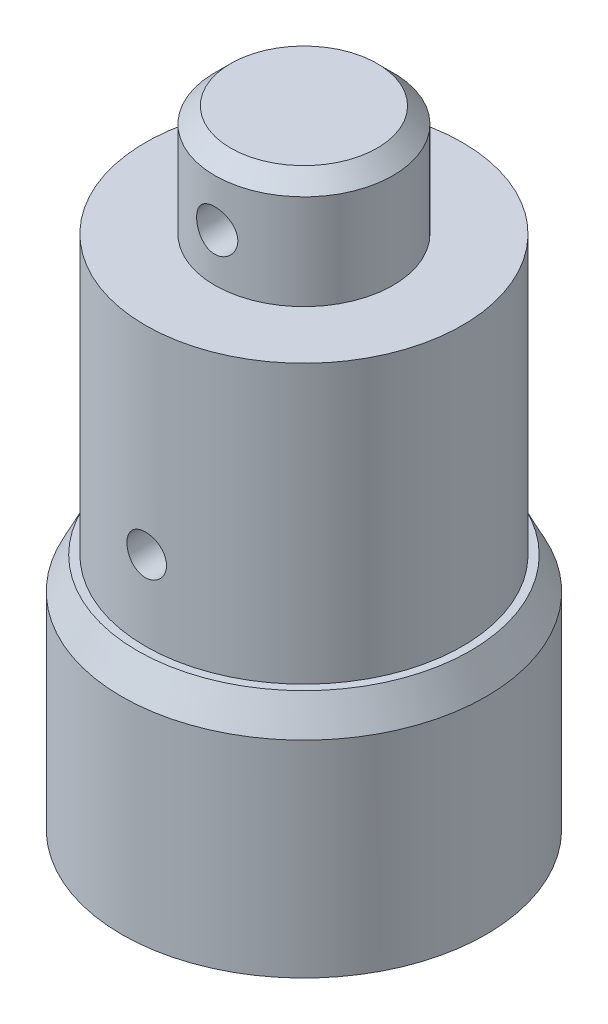
SolidWorks part; units mm, degrees
material "Custom Plastic"
ref_plane "Front Plane" through (0, 0, 0) normal (0, 0, 1) x (1, 0, 0)
ref_plane "Top Plane" through (0, 0, 0) normal (0, 1, 0) x (1, 0, 0)
ref_plane "Right Plane" through (0, 0, 0) normal (1, 0, 0) x (0, 0, -1)
sketch "Sketch1" plane through (0, 0, 0) normal (0, 1, 0) x (1, 0, 0)
  circle A0 centre (0, 0) radius 12.7
  dimension "D1" = 25.4
extrude "Boss-Extrude1" add sketch "Sketch1" along normal blind 31.1658
sketch "Sketch2" plane through (0, 0, 0) normal (0, -1, 0) x (1, 0, 0)
  circle A0 centre (0, 0) radius 3.2385
  circle M2 centre (0, 0) radius 12.7
  dimension "D1" = 6.477
extrude "Cut-Extrude1" cut sketch "Sketch2" against normal blind 12.7 contours A0 M2
sketch "Sketch3" plane through (0, 31.1658, 0) normal (0, 1, 0) x (1, 0, 0)
  circle A0 centre (0, 0) radius 7.1438
  circle M2 centre (0, 0) radius 12.7
  dimension "D1" = 14.2875
extrude "Cut-Extrude2" cut sketch "Sketch3" against normal blind 8.89 contours A0 M2
chamfer "Chamfer1" distance 1.27 angle 45 2 edges at (0, 0, -3.2385) (0, 31.1658, 7.1438)
sketch "Sketch4" plane through (0, 0, 0) normal (0, -1, 0) x (1, 0, 0)
  circle A0 centre (0, 0) radius 12.7
  circle A1 centre (0, 0) radius 7.747
  circle A2 centre (0, 0) radius 12.7 construction
  dimension "D1" = 15.494
extrude "Boss-Extrude2" add sketch "Sketch4" against normal offset from surface (15.24 mm away) 2.54 up to face at (0, 12.7, -3.2385) offset beyond the face yes
chamfer "Chamfer2" distance 2.54 angle 45 1 edges at (0, 0, -7.747)
sketch "Sketch6" plane through (0, 0, 0) normal (0, 0, 1) x (1, 0, 0)
  line L0 (-12.7, 0) -> (12.7, 0) construction
  line L1 (12.7, 22.2758) -> (-12.7, 22.2758) construction
  circle A0 centre (0, 6.35) radius 1.5875
  circle A1 centre (0, 26.0858) radius 1.651
  dimension "D1" = 3.175
  dimension "D3" = 3.302
  dimension "D2" = 6.35
  dimension "D4" = 3.81
extrude "Cut-Extrude3" cut sketch "Sketch6" against normal mid plane 101.6
sketch "Sketch7" plane through (0, 0, 0) normal (0, -1, 0) x (1, 0, 0)
  circle A0 centre (0, 0) radius 10.795
  circle A1 centre (0, 0) radius 14.605
  dimension "D1" = 21.59
  dimension "D2" = 29.21
extrude "Boss-Extrude3" add sketch "Sketch7" along normal blind 19.05
chamfer "Chamfer3" distance 1.27 distance2 2.54 2 edges at (0, -19.05, -10.795) (0, 0, -14.605)
